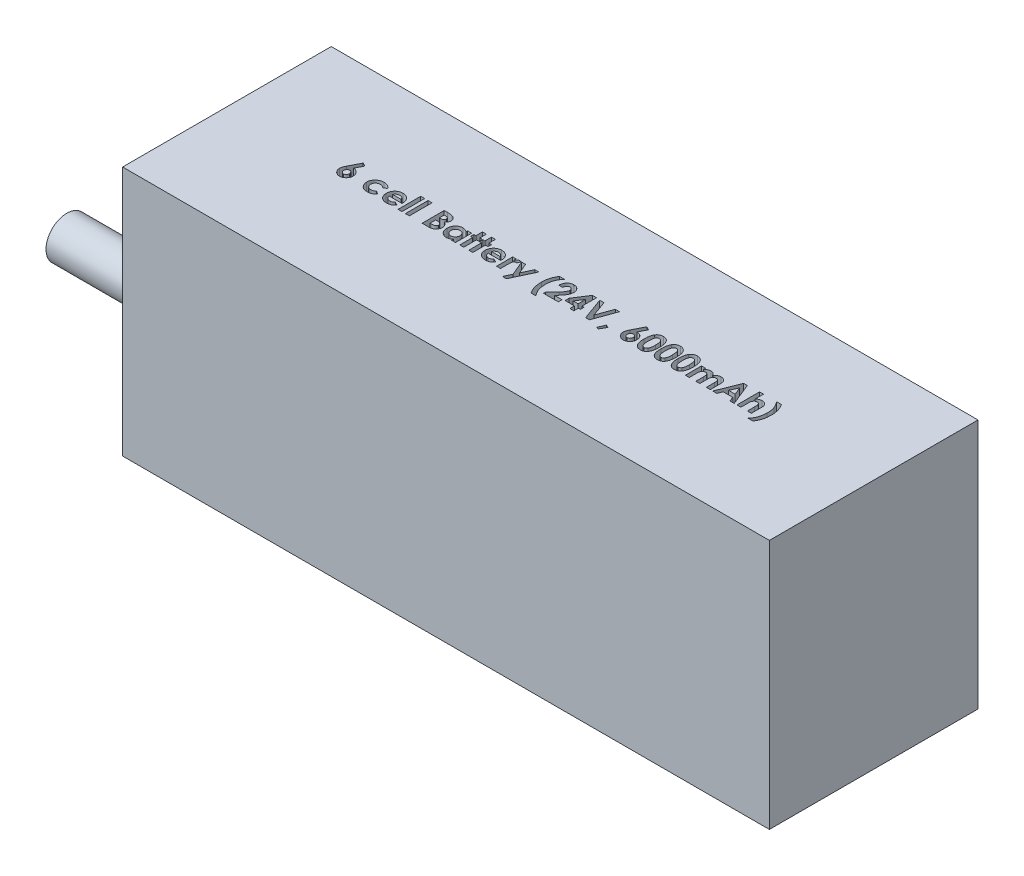
SolidWorks part; units mm, degrees
ref_plane "Front Plane" through (0, 0, 0) normal (0, 0, 1) x (1, 0, 0)
ref_plane "Top Plane" through (0, 0, 0) normal (0, 1, 0) x (1, 0, 0)
ref_plane "Right Plane" through (0, 0, 0) normal (1, 0, 0) x (0, 0, -1)
sketch "Sketch1" plane through (0, 0, 0) normal (0, 1, 0) x (1, 0, 0)
  line L1 (0, 0) -> (155, 0)
  line L2 (0, 0) -> (0, 50)
  line L3 (0, 50) -> (155, 50)
  line L4 (155, 0) -> (155, 50)
  dimension "D1" = 155
  dimension "D2" = 50
extrude "Boss-Extrude1" add sketch "Sketch1" along normal blind 60
sketch "Sketch2" plane through (0, 0, 0) normal (-1, 0, 0) x (0, 0, 1)
  line L0 (-50, 0) -> (0, 0) construction
  line L1 (0, 60) -> (0, 0) construction
  circle A0 centre (-45.4509, 32.0886) radius 2.5
  circle A1 centre (-6.6377, 32.0886) radius 5
  dimension "D1" = 10
  dimension "D2" = 5
  dimension "D3" = 6.6377
  dimension "D4" = 45.4509
  dimension "D5" = 32.0886
extrude "Boss-Extrude2" add sketch "Sketch2" along normal blind 20
sketch "Sketch3" plane through (0, 60, 0) normal (0, 1, 0) x (1, 0, 0)
  text T0 "6 cell Battery (24V, 6000mAh)" font "Century Gothic" height in points 20
extrude "Cut-Extrude1" cut sketch "Sketch3" against normal blind 5
